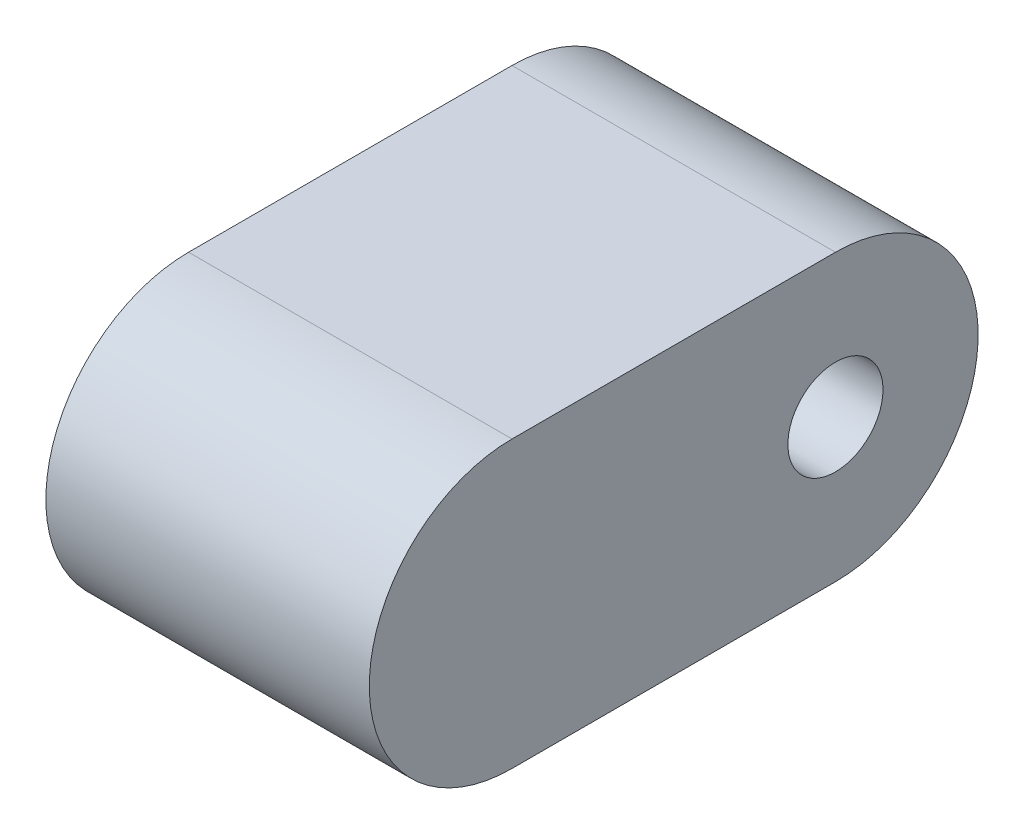
SolidWorks part; units mm, degrees
ref_plane "Alzado" through (0, 0, 0) normal (0, 0, 1) x (1, 0, 0)
ref_plane "Planta" through (0, 0, 0) normal (0, 1, 0) x (1, 0, 0)
ref_plane "Vista lateral" through (0, 0, 0) normal (1, 0, 0) x (0, 0, -1)
sketch "Croquis1" plane through (0, 0, 0) normal (1, 0, 0) x (0, 0, -1)
  line L0 (0, 7.5) -> (-17, 7.5)
  line L1 (0, -7.5) -> (-17, -7.5)
  circle A0 centre (0, 0) radius 2.5
  arc A1 (0, -7.5) -> (0, 7.5) centre (0, 0) ccw
  arc A2 (-17, 7.5) -> (-17, -7.5) centre (-17, 0) ccw
  point P7 (0, 0)
  dimension "D2" = 15
  dimension "D1" = 17
  dimension "D3" = 5
extrude "Saliente-Extruir1" add sketch "Croquis1" along normal mid plane 17
sketch "Croquis2" plane through (0, 0, 0) normal (0, 1, 0) x (1, 0, 0)
  line L0 (8.5, 7.5) -> (-8.5, 7.5) construction
  line L1 (2.8333, 7.5) -> (-2.8333, 7.5)
  line L2 (2.8333, 7.5) -> (2.8333, -8.5)
  line L3 (2.8333, -8.5) -> (-2.8333, -8.5)
  line L4 (-2.8333, 7.5) -> (-2.8333, -8.5)
  line L5 (8.5, 0) -> (8.5, -17) construction
  point P6 (0, 7.5)
  point P10 (8.5, -8.5)
  dimension "D1" = 5.6667
